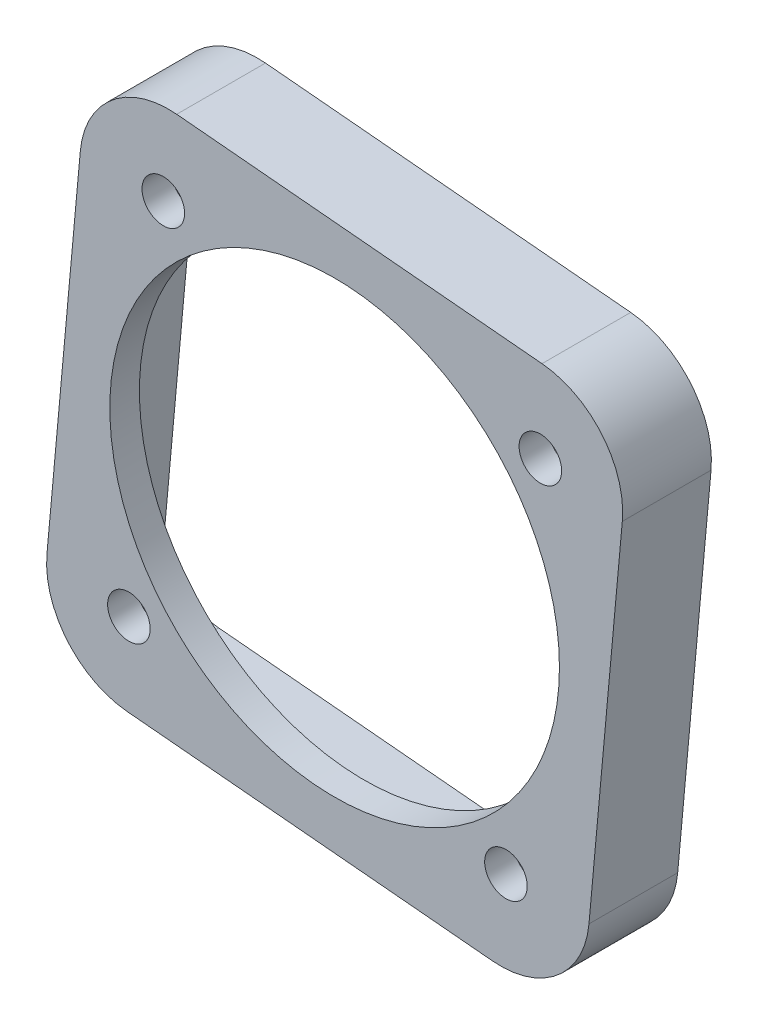
SolidWorks part; units mm, degrees
material "ABS"
ref_plane "X-Y Datum" through (0, 0, 0) normal (0, 0, 1) x (1, 0, 0)
ref_plane "X-Z Datum" through (0, 0, 0) normal (0, 1, 0) x (1, 0, 0)
ref_plane "Y-Z Datum" through (0, 0, 0) normal (1, 0, 0) x (0, 0, -1)
sketch "Sketch2" plane through (0, 0, -2122.6666) normal (0, 0, 1) x (1, 0, 0)
  line L0 (127.4318, 119.7896) -> (130.2492, 150.6613) construction
  line L1 (162.3759, 112.0819) -> (131.5042, 114.8992) construction
  line L2 (167.5614, 119.388) -> (167.2662, 116.1543) construction
  line L3 (167.7207, 121.1336) -> (167.5614, 119.388) construction
  line L4 (167.7207, 121.1336) -> (167.7479, 121.4323) construction
  line L5 (167.9297, 123.4241) -> (167.957, 123.7228) construction
  line L6 (168.2387, 126.81) -> (167.957, 123.7228) construction
  line L7 (170.0836, 147.026) -> (168.2387, 126.81) construction
  line L8 (135.1395, 154.7337) -> (166.0112, 151.9163) construction
  line L9 (127.4318, 119.7896) -> (130.2492, 150.6613) construction
  line L10 (162.3759, 112.0819) -> (131.5042, 114.8992) construction
  line L11 (167.5614, 119.388) -> (167.2662, 116.1543) construction
  line L12 (167.7207, 121.1336) -> (167.5614, 119.388) construction
  line L13 (167.7207, 121.1336) -> (167.7479, 121.4323) construction
  line L14 (167.9297, 123.4241) -> (167.957, 123.7228) construction
  line L15 (168.2387, 126.81) -> (167.957, 123.7228) construction
  line L16 (170.0836, 147.026) -> (168.2387, 126.81) construction
  line L17 (135.1395, 154.7337) -> (166.0112, 151.9163) construction
  line L18 (167.9297, 123.4241) -> (167.7479, 121.4323) construction
  line L19 (168.7366, 126.7645) -> (168.4549, 123.6774)
  line L20 (168.4276, 123.3786) -> (168.4549, 123.6774)
  line L21 (168.4276, 123.3786) -> (168.2459, 121.3869)
  line L22 (168.2186, 121.0881) -> (168.2459, 121.3869)
  line L23 (168.2186, 121.0881) -> (168.0593, 119.3426)
  line L24 (168.0593, 119.3426) -> (167.7642, 116.1088)
  line L25 (162.3305, 111.5839) -> (131.4587, 114.4013)
  line L26 (126.9339, 119.835) -> (129.7512, 150.7067)
  line L27 (135.1849, 155.2316) -> (166.0567, 152.4143)
  line L28 (170.5815, 146.9805) -> (168.7366, 126.7645)
  line L29 (135.4122, 157.7213) -> (166.2839, 154.9039)
  line L30 (173.0712, 146.7533) -> (171.2263, 126.5373)
  line L31 (171.2263, 126.5373) -> (170.9445, 123.4502)
  line L32 (170.9173, 123.1514) -> (170.9445, 123.4502)
  line L33 (170.9173, 123.1514) -> (170.7355, 121.1597)
  line L34 (170.7082, 120.8609) -> (170.7355, 121.1597)
  line L35 (170.7082, 120.8609) -> (170.5489, 119.1154)
  line L36 (170.5489, 119.1154) -> (170.2538, 115.8816)
  line L37 (162.1033, 109.0943) -> (131.2315, 111.9116)
  line L38 (124.4442, 120.0622) -> (127.2616, 150.9339)
  line L39 (127.1828, 119.8123) -> (130.0002, 150.684)
  line L40 (162.3532, 111.8329) -> (131.4815, 114.6503)
  line L41 (167.8103, 119.3653) -> (167.5152, 116.1315)
  line L42 (167.9696, 121.1108) -> (167.8103, 119.3653)
  line L43 (167.9696, 121.1108) -> (167.9969, 121.4096)
  line L44 (168.1787, 123.4013) -> (167.9969, 121.4096)
  line L45 (168.1787, 123.4013) -> (168.2059, 123.7001)
  line L46 (168.4877, 126.7873) -> (168.2059, 123.7001)
  line L47 (170.3326, 147.0033) -> (168.4877, 126.7873)
  line L48 (135.1622, 154.9827) -> (166.0339, 152.1653)
  arc A0 (164.1041, 148.0737) -> (168.1871, 147.7011) centre (166.1456, 147.8874) ccw construction
  arc A1 (168.1871, 147.7011) -> (164.1041, 148.0737) centre (166.1456, 147.8874) ccw construction
  arc A2 (161.1958, 116.2062) -> (165.2789, 115.8336) centre (163.2374, 116.0199) ccw construction
  arc A3 (165.2789, 115.8336) -> (161.1958, 116.2062) centre (163.2374, 116.0199) ccw construction
  arc A4 (129.3283, 119.1144) -> (133.4113, 118.7418) centre (131.3698, 118.9281) ccw construction
  arc A5 (133.4113, 118.7418) -> (129.3283, 119.1144) centre (131.3698, 118.9281) ccw construction
  arc A6 (132.2365, 150.982) -> (136.3196, 150.6094) centre (134.278, 150.7957) ccw construction
  arc A7 (136.3196, 150.6094) -> (132.2365, 150.982) centre (134.278, 150.7957) ccw construction
  arc A8 (127.4318, 119.7896) -> (131.5042, 114.8992) centre (131.9132, 119.3806) ccw construction
  arc A9 (162.3759, 112.0819) -> (167.2662, 116.1543) centre (162.7849, 116.5632) ccw construction
  arc A10 (170.0836, 147.026) -> (166.0112, 151.9163) centre (165.6022, 147.4349) ccw construction
  arc A11 (135.1395, 154.7337) -> (130.2492, 150.6613) centre (134.7305, 150.2523) ccw construction
  arc A12 (164.1041, 148.0737) -> (168.1871, 147.7011) centre (166.1456, 147.8874) ccw construction
  arc A13 (168.1871, 147.7011) -> (164.1041, 148.0737) centre (166.1456, 147.8874) ccw construction
  arc A14 (161.1958, 116.2062) -> (165.2789, 115.8336) centre (163.2374, 116.0199) ccw construction
  arc A15 (165.2789, 115.8336) -> (161.1958, 116.2062) centre (163.2374, 116.0199) ccw construction
  arc A16 (129.3283, 119.1144) -> (133.4113, 118.7418) centre (131.3698, 118.9281) ccw construction
  arc A17 (133.4113, 118.7418) -> (129.3283, 119.1144) centre (131.3698, 118.9281) ccw construction
  arc A18 (132.2365, 150.982) -> (136.3196, 150.6094) centre (134.278, 150.7957) ccw construction
  arc A19 (136.3196, 150.6094) -> (132.2365, 150.982) centre (134.278, 150.7957) ccw construction
  arc A20 (127.4318, 119.7896) -> (131.5042, 114.8992) centre (131.9132, 119.3806) ccw construction
  arc A21 (162.3759, 112.0819) -> (167.2662, 116.1543) centre (162.7849, 116.5632) ccw construction
  arc A22 (170.0836, 147.026) -> (166.0112, 151.9163) centre (165.6022, 147.4349) ccw construction
  arc A23 (135.1395, 154.7337) -> (130.2492, 150.6613) centre (134.7305, 150.2523) ccw construction
  arc A24 (162.3305, 111.5839) -> (167.7642, 116.1088) centre (162.7849, 116.5632) ccw
  arc A25 (126.9339, 119.835) -> (131.4587, 114.4013) centre (131.9132, 119.3806) ccw
  arc A26 (135.1849, 155.2316) -> (129.7512, 150.7067) centre (134.7305, 150.2523) ccw
  arc A27 (170.5815, 146.9805) -> (166.0567, 152.4143) centre (165.6022, 147.4349) ccw
  arc A28 (173.0712, 146.7533) -> (166.2839, 154.9039) centre (165.6022, 147.4349) ccw
  arc A29 (162.1033, 109.0943) -> (170.2538, 115.8816) centre (162.7849, 116.5632) ccw
  arc A30 (124.4442, 120.0622) -> (131.2315, 111.9116) centre (131.9132, 119.3806) ccw
  arc A31 (135.4122, 157.7213) -> (127.2616, 150.9339) centre (134.7305, 150.2523) ccw
  arc A32 (129.7838, 134.4027) -> (129.7588, 133.6103) centre (148.7577, 133.4078) ccw construction
  arc A33 (129.7588, 133.6103) -> (131.7102, 125.0183) centre (148.7577, 133.4078) ccw construction
  arc A34 (137.0704, 148.388) -> (131.5696, 141.5053) centre (148.7577, 133.4078) ccw construction
  arc A35 (129.7838, 134.4027) -> (129.7588, 133.6103) centre (148.7577, 133.4078) ccw
  arc A36 (129.7588, 133.6103) -> (131.7102, 125.0183) centre (148.7577, 133.4078) ccw
  arc A37 (137.0704, 148.388) -> (131.5696, 141.5053) centre (148.7577, 133.4078) ccw
  circle A38 centre (148.7577, 133.4078) radius 19
  arc A39 (135.1622, 154.9827) -> (130.0002, 150.684) centre (134.7305, 150.2523) ccw
  arc A40 (127.1828, 119.8123) -> (131.4815, 114.6503) centre (131.9132, 119.3806) ccw
  arc A41 (162.3532, 111.8329) -> (167.5152, 116.1315) centre (162.7849, 116.5632) ccw
  arc A42 (170.3326, 147.0033) -> (166.0339, 152.1653) centre (165.6022, 147.4349) ccw
  dimension "D1" = 0.5
  dimension "D2" = 2.5
  dimension "D3" = 0.25
extrude "Boss-Extrude2" add sketch "Sketch2" along normal blind 2.5 contours L47 A42 L48 A39 L39 A40 L40 A41 L41 L42 L43 L44 L45 L46 A38 A37 A36 A35 | L28 A27 L27 A26 L26 A25 L25 A24 L24 L23 L22 L21 L20 L19 A42 L47 L46 L45 L44 L43 L42 L41 A41 L40 A40 L39 A39 L48 | L29 A31 L38 A30 L37 A29 L36 L35 L34 L33 L32 L31 L30 A28 A27 L28 L19 L20 L21 L22 L23 L24 A24 L25 A25 L26 A26 L27
sketch "Sketch4" plane through (0, 0, -2122.6666) normal (0, 0, -1) x (-1, 0, 0)
  line L0 (-135.1849, 155.2316) -> (-166.0567, 152.4143)
  line L1 (-170.5815, 146.9805) -> (-167.7642, 116.1088)
  line L2 (-162.3305, 111.5839) -> (-131.4587, 114.4013)
  line L3 (-126.9339, 119.835) -> (-129.7512, 150.7067)
  line L4 (-135.4122, 157.7213) -> (-166.2839, 154.9039)
  line L5 (-173.0712, 146.7533) -> (-170.2538, 115.8816)
  line L6 (-162.1033, 109.0943) -> (-131.2315, 111.9116)
  line L7 (-124.4442, 120.0622) -> (-127.2616, 150.9339)
  line L8 (-135.4122, 157.7213) -> (-166.2839, 154.9039)
  line L9 (-173.0712, 146.7533) -> (-170.2538, 115.8816)
  line L10 (-162.1033, 109.0943) -> (-131.2315, 111.9116)
  line L11 (-124.4442, 120.0622) -> (-127.2616, 150.9339)
  arc A0 (-166.0567, 152.4143) -> (-170.5815, 146.9805) centre (-165.6022, 147.4349) ccw
  arc A1 (-167.7642, 116.1088) -> (-162.3305, 111.5839) centre (-162.7849, 116.5632) ccw
  arc A2 (-131.4587, 114.4013) -> (-126.9339, 119.835) centre (-131.9132, 119.3806) ccw
  arc A3 (-129.7512, 150.7067) -> (-135.1849, 155.2316) centre (-134.7305, 150.2523) ccw
  arc A4 (-166.2839, 154.9039) -> (-173.0712, 146.7533) centre (-165.6022, 147.4349) ccw
  arc A5 (-170.2538, 115.8816) -> (-162.1033, 109.0943) centre (-162.7849, 116.5632) ccw
  arc A6 (-131.2315, 111.9116) -> (-124.4442, 120.0622) centre (-131.9132, 119.3806) ccw
  arc A7 (-127.2616, 150.9339) -> (-135.4122, 157.7213) centre (-134.7305, 150.2523) ccw
  arc A8 (-166.2839, 154.9039) -> (-173.0712, 146.7533) centre (-165.6022, 147.4349) ccw
  arc A9 (-170.2538, 115.8816) -> (-162.1033, 109.0943) centre (-162.7849, 116.5632) ccw
  arc A10 (-131.2315, 111.9116) -> (-124.4442, 120.0622) centre (-131.9132, 119.3806) ccw
  arc A11 (-127.2616, 150.9339) -> (-135.4122, 157.7213) centre (-134.7305, 150.2523) ccw
  dimension "D1" = 0
  dimension "D2" = 2.5
extrude "Boss-Extrude3" add sketch "Sketch4" along normal blind 5
hole_wizard "M3 Clearance Hole1" positions "Sketch9" profile "Sketch8" hole size "M3" standard "ANSI Metric" end condition up to next
sketch "Sketch9" plane through (0, 0, -2120.1666) normal (0, 0, 1) x (1, 0, 0)
  point P0 (134.278, 150.7957)
  point P3 (131.3698, 118.9281)
  point P6 (163.2374, 116.0199)
  point P9 (166.1456, 147.8874)
sketch "Sketch8" plane through (134.278, 150.7957, -2120.1666) normal (1, 0, 0) x (0, -1, 0)
  line L0 (0, 0) -> (0, 2.5)
  line L1 (0, 2.5) -> (1.8, 2.5)
  line L2 (1.8, 2.5) -> (1.8, 0)
  line L5 (1.8, 0) -> (0, 0)
  line L11 (0, -6.35) -> (0, 107.95) construction
  dimension "Thru Hole Dia." = 3.6
  dimension "Thru Hole Depth" = 2.5
